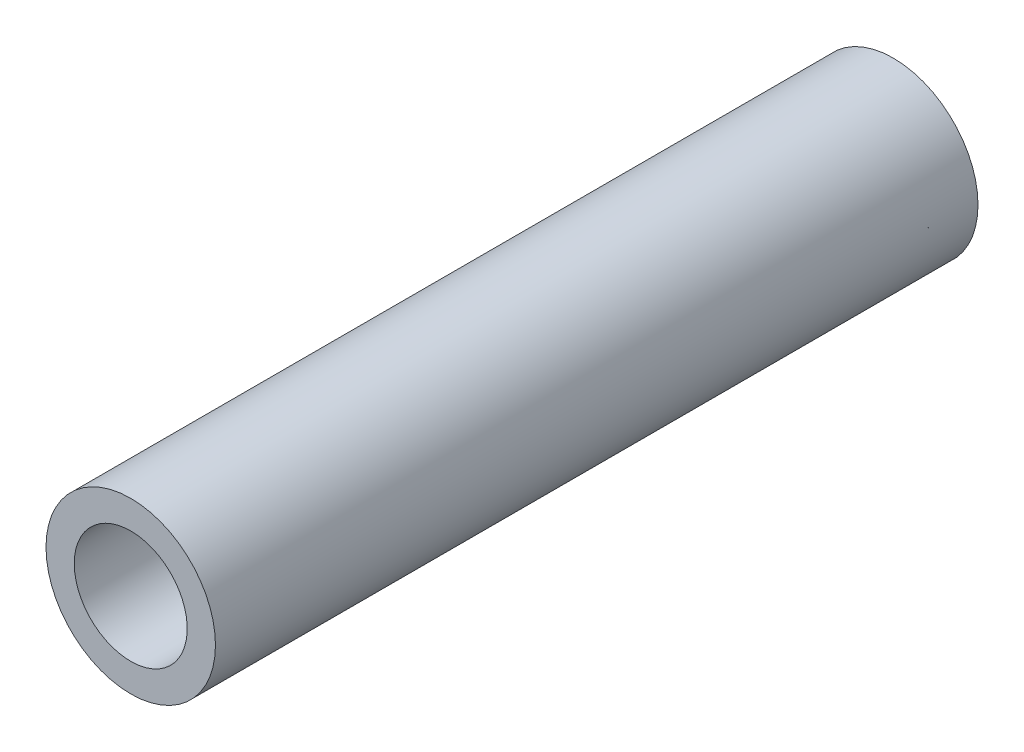
SolidWorks part; units mm, degrees
material "C-Fibra di vetro"
ref_plane "Piano frontale" through (0, 0, 0) normal (0, 0, 1) x (1, 0, 0)
ref_plane "Piano superiore" through (0, 0, 0) normal (0, 1, 0) x (1, 0, 0)
ref_plane "Piano destro" through (0, 0, 0) normal (1, 0, 0) x (0, 0, -1)
sketch "Schizzo2" plane through (0, 0, 0) normal (0, 0, 1) x (1, 0, 0)
  circle A0 centre (13, -54.5) radius 3
  circle A1 centre (13, -54.5) radius 2
  dimension "D1" = 6
  dimension "D2" = 1
extrude "Estrusione-Estrusione1" add sketch "Schizzo2" along normal up to surface (27 mm away)
